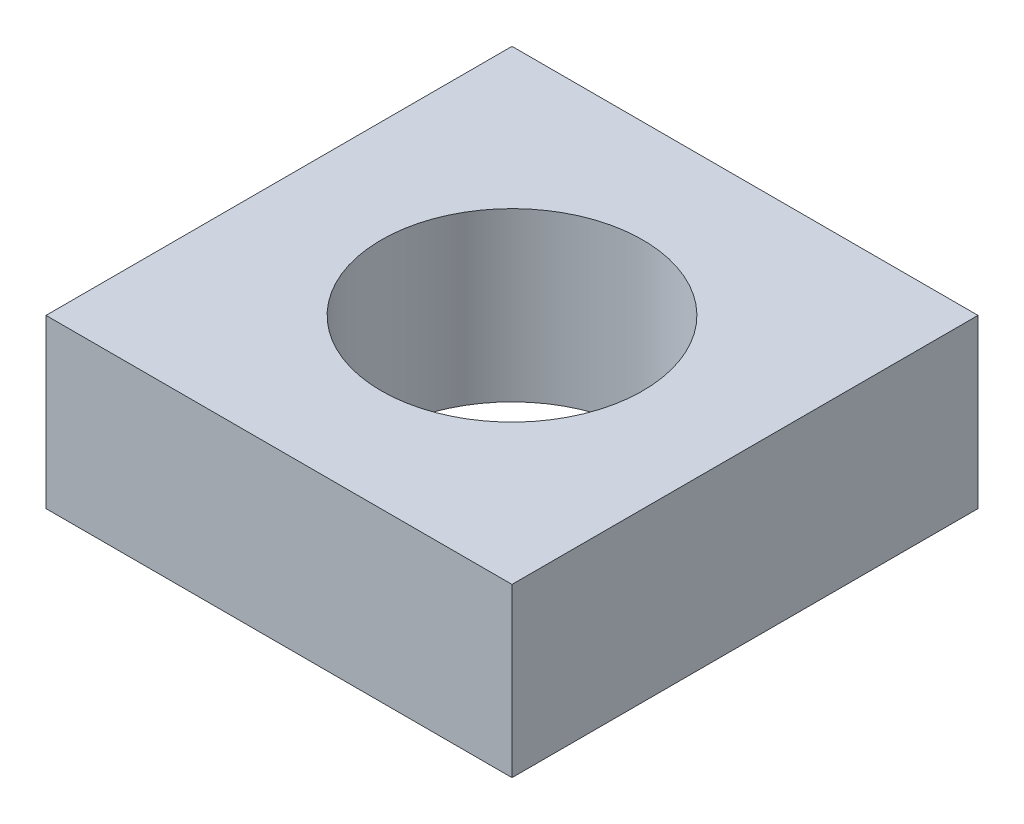
SolidWorks part; units mm, degrees
ref_plane "Płaszczyzna przednia" through (0, 0, 0) normal (0, 0, 1) x (1, 0, 0)
ref_plane "Płaszczyzna górna" through (0, 0, 0) normal (0, 1, 0) x (1, 0, 0)
ref_plane "Płaszczyzna prawa" through (0, 0, 0) normal (1, 0, 0) x (0, 0, -1)
sketch "Szkic1" plane through (0, 0, 0) normal (0, 1, 0) x (1, 0, 0)
  line L0 (0, 0) -> (4.4548, 4.4548) construction
  line L1 (0, 0) -> (4.4548, 0)
  line L2 (0, 0) -> (0, 4.4548)
  line L3 (0, 4.4548) -> (4.4548, 4.4548)
  line L4 (4.4548, 0) -> (4.4548, 4.4548)
  circle A0 centre (2.2274, 2.2274) radius 1.25
extrude "Dodanie-wyciągnięcie1" add sketch "Szkic1" along normal blind 1.6
